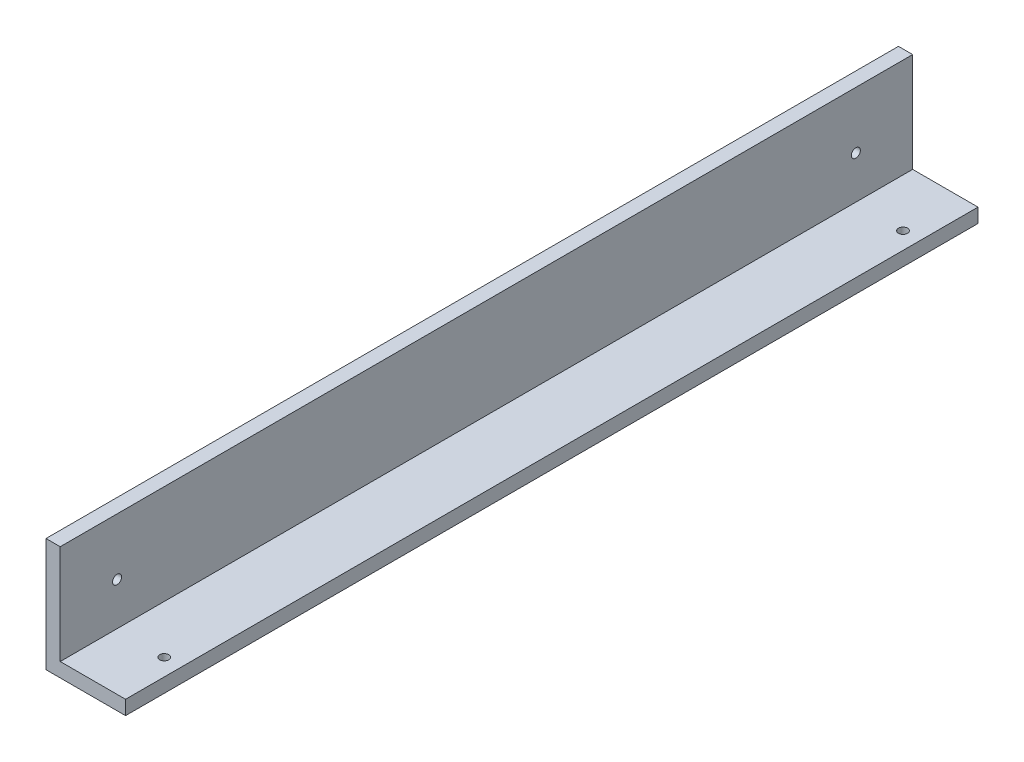
SolidWorks part; units mm, degrees
material "1060 Alloy"
ref_plane "Front Plane" through (0, 0, 0) normal (0, 0, 1) x (1, 0, 0)
ref_plane "Top Plane" through (0, 0, 0) normal (0, 1, 0) x (1, 0, 0)
ref_plane "Right Plane" through (0, 0, 0) normal (1, 0, 0) x (0, 0, -1)
sketch "Sketch1" plane through (0, 0, 0) normal (0, 0, 1) x (1, 0, 0)
  line L0 (0, 0) -> (0, 50.8)
  line L1 (0, 0) -> (35.56, 0)
  line L2 (35.56, 0) -> (35.56, 6.35)
  line L3 (0, 50.8) -> (6.35, 50.8)
  line L4 (6.35, 50.8) -> (6.35, 6.35)
  line L5 (6.35, 6.35) -> (35.56, 6.35)
extrude "Boss-Extrude1" add sketch "Sketch1" along normal blind 381
sketch "Sketch7" plane through (0, 6.35, 0) normal (0, 1, 0) x (1, 0, 0)
  line L3 (27.94, -41.1353) -> (27.94, -371.3353) construction
hole_wizard "#10-32 Tapped Hole5" positions "Sketch14" profile "Sketch13" tap size "#10-32" standard "Ansi Inch" end condition through all
sketch "Sketch14" plane through (6.35, 0, 0) normal (1, 0, 0) x (0, 0, -1)
  line L5 (-381, 50.8) -> (-381, 25.4) construction
  line L6 (-381, 6.35) -> (-381, 50.8) construction
  point P21 (-355.6, 25.4)
  point P27 (-25.4, 25.4)
sketch "Sketch13" plane through (6.35, 25.4, 355.6) normal (0, 1, 0) x (0, 0, -1)
  line L0 (0, 0) -> (0, 6.35)
  line L1 (0, 6.35) -> (2.0193, 6.35)
  line L2 (2.0193, 6.35) -> (2.0193, 0)
  line L5 (2.0193, 0) -> (0, 0)
  line L11 (0, -6.35) -> (0, 107.95) construction
  dimension "Thru Tap Drill Dia." = 4.0386
  dimension "Thru Tap Drill Depth" = 6.35
cosmetic thread "Hole Thread8" parameters "D2"=4.826
cosmetic thread "Hole Thread9" parameters "D2"=4.826
hole_wizard "#10-32 Tapped Hole6" positions "Sketch16" profile "Sketch15" tap size "#10-32" standard "Ansi Inch" end condition through all
sketch "Sketch16" plane through (0, 6.35, 0) normal (0, 1, 0) x (-1, 0, 0)
  point P3 (-27.94, 356.0953)
  point P6 (-27.94, 25.8953)
sketch "Sketch15" plane through (27.94, 6.35, 356.0953) normal (1, 0, 0) x (0, 0, 1)
  line L0 (0, 0) -> (0, 6.35)
  line L1 (0, 6.35) -> (2.0193, 6.35)
  line L2 (2.0193, 6.35) -> (2.0193, 0)
  line L5 (2.0193, 0) -> (0, 0)
  line L11 (0, -6.35) -> (0, 107.95) construction
  dimension "Thru Tap Drill Dia." = 4.0386
  dimension "Thru Tap Drill Depth" = 6.35
cosmetic thread "Hole Thread10" parameters "D2"=4.826
cosmetic thread "Hole Thread11" parameters "D2"=4.826
